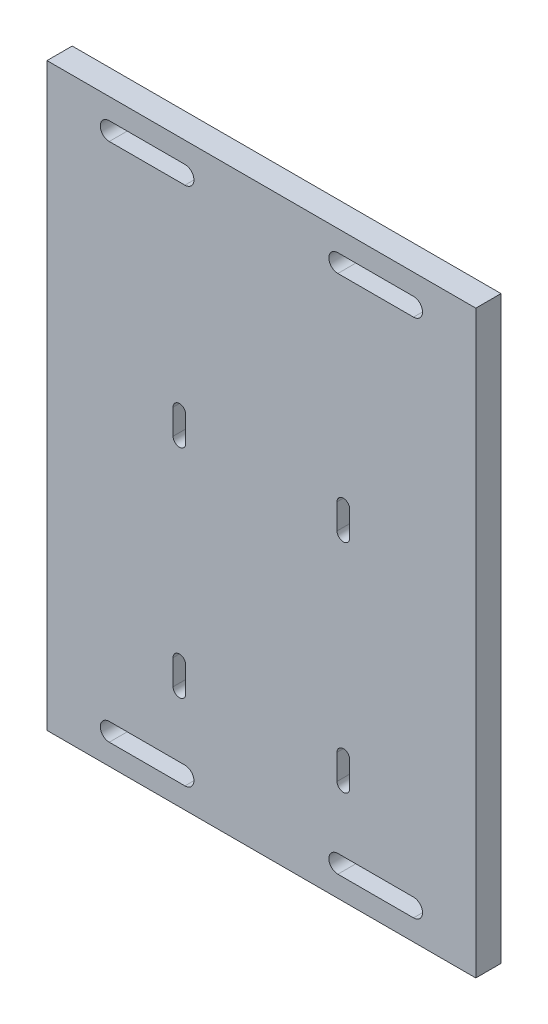
SolidWorks part; units mm, degrees
ref_plane "Front Plane" through (0, 0, 0) normal (0, 0, 1) x (1, 0, 0)
ref_plane "Top Plane" through (0, 0, 0) normal (0, 1, 0) x (1, 0, 0)
ref_plane "Right Plane" through (0, 0, 0) normal (1, 0, 0) x (0, 0, -1)
sketch "Sketch1" plane through (0, 0, 0) normal (0, 0, 1) x (1, 0, 0)
  line L1 (85, -115) -> (85, 115)
  line L2 (85, 115) -> (-85, 115)
  line L3 (85, -115) -> (-85, -115)
  line L5 (-85, -115) -> (-85, 115)
  line L7 (30.3147, 106.6958) -> (60.3147, 106.6958)
  line L9 (30.3147, 99.5629) -> (60.3147, 99.5629)
  line L11 (35, -75) -> (35, -65)
  line L12 (30, -75) -> (30, -65)
  line L14 (-30.3147, 106.6958) -> (-60.3147, 106.6958)
  line L15 (30, 21) -> (30, 11)
  line L16 (35, 21) -> (35, 11)
  line L17 (-30, 21) -> (-30, 11)
  line L18 (-35, 21) -> (-35, 11)
  line L19 (-30, -75) -> (-30, -65)
  line L20 (-35, -75) -> (-35, -65)
  line L21 (-30.3147, 99.5629) -> (-60.3147, 99.5629)
  line L22 (-30.3147, -99.5629) -> (-60.3147, -99.5629)
  line L23 (-30.3147, -106.6958) -> (-60.3147, -106.6958)
  line L24 (30.3147, -99.5629) -> (60.3147, -99.5629)
  line L25 (30.3147, -106.6958) -> (60.3147, -106.6958)
  arc A0 (60.3147, 99.5629) -> (60.3147, 106.6958) centre (60.3147, 103.1294) ccw
  arc A1 (30.3147, 106.6958) -> (30.3147, 99.5629) centre (30.3147, 103.1294) ccw
  arc A2 (30, -75) -> (35, -75) centre (32.5, -75) ccw
  arc A3 (35, -65) -> (30, -65) centre (32.5, -65) ccw
  arc A4 (30, 21) -> (35, 21) centre (32.5, 21) cw
  arc A5 (35, 11) -> (30, 11) centre (32.5, 11) cw
  arc A6 (-30, 21) -> (-35, 21) centre (-32.5, 21) ccw
  arc A7 (-35, 11) -> (-30, 11) centre (-32.5, 11) ccw
  arc A8 (-30, -75) -> (-35, -75) centre (-32.5, -75) cw
  arc A9 (-35, -65) -> (-30, -65) centre (-32.5, -65) cw
  arc A10 (-30.3147, 106.6958) -> (-30.3147, 99.5629) centre (-30.3147, 103.1294) cw
  arc A11 (-60.3147, 99.5629) -> (-60.3147, 106.6958) centre (-60.3147, 103.1294) cw
  arc A12 (-30.3147, -106.6958) -> (-30.3147, -99.5629) centre (-30.3147, -103.1294) ccw
  arc A13 (-60.3147, -99.5629) -> (-60.3147, -106.6958) centre (-60.3147, -103.1294) ccw
  arc A14 (60.3147, -99.5629) -> (60.3147, -106.6958) centre (60.3147, -103.1294) cw
  arc A15 (30.3147, -106.6958) -> (30.3147, -99.5629) centre (30.3147, -103.1294) cw
  dimension "D3" = 30
extrude "Boss-Extrude1" add sketch "Sketch1" along normal blind 10
